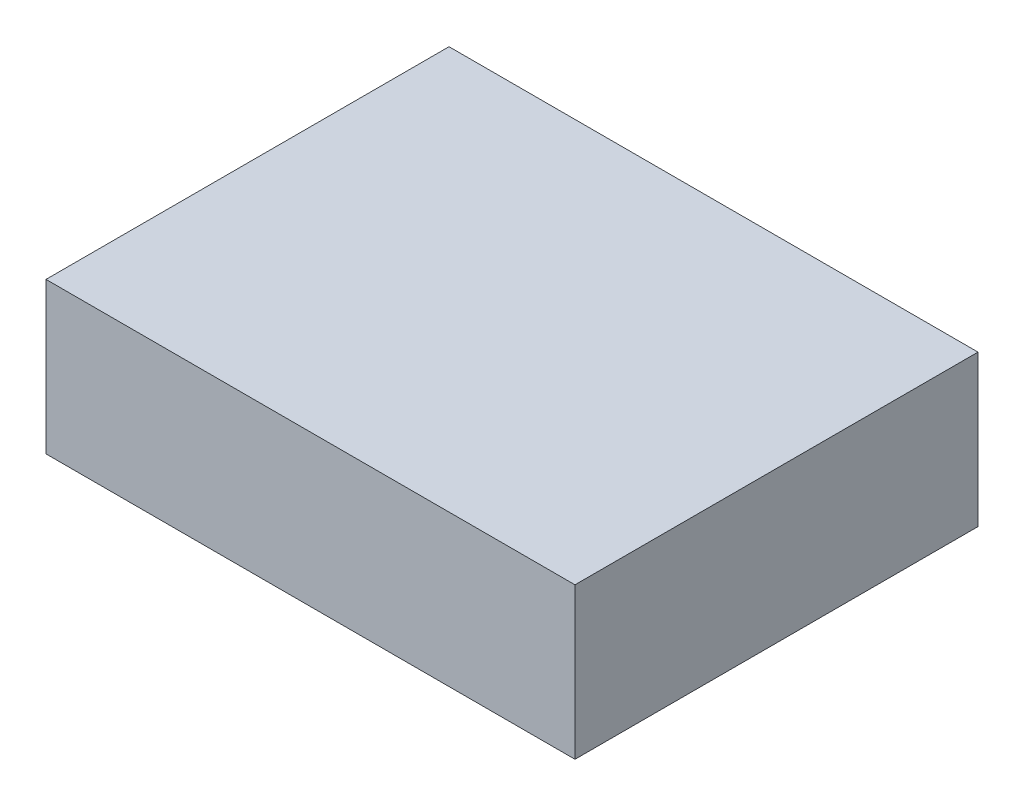
SolidWorks part; units mm, degrees
ref_plane "Front Plane" through (0, 0, 0) normal (0, 0, 1) x (1, 0, 0)
ref_plane "Top Plane" through (0, 0, 0) normal (0, 1, 0) x (1, 0, 0)
ref_plane "Right Plane" through (0, 0, 0) normal (1, 0, 0) x (0, 0, -1)
sketch "Sketch3" plane through (0, 0, 0) normal (0, 0, 1) x (1, 0, 0)
  line L1 (-21, 6) -> (21, 6)
  line L2 (-21, 6) -> (-21, -6)
  line L3 (-21, -6) -> (21, -6)
  line L4 (21, 6) -> (21, -6)
  line L5 (-21, 6) -> (21, -6) construction
  line L6 (-21, -6) -> (21, 6) construction
  point P0 (0, 0)
  dimension "D1" = 12
  dimension "D2" = 42
extrude "Boss-Extrude1" add sketch "Sketch3" against normal blind 32
